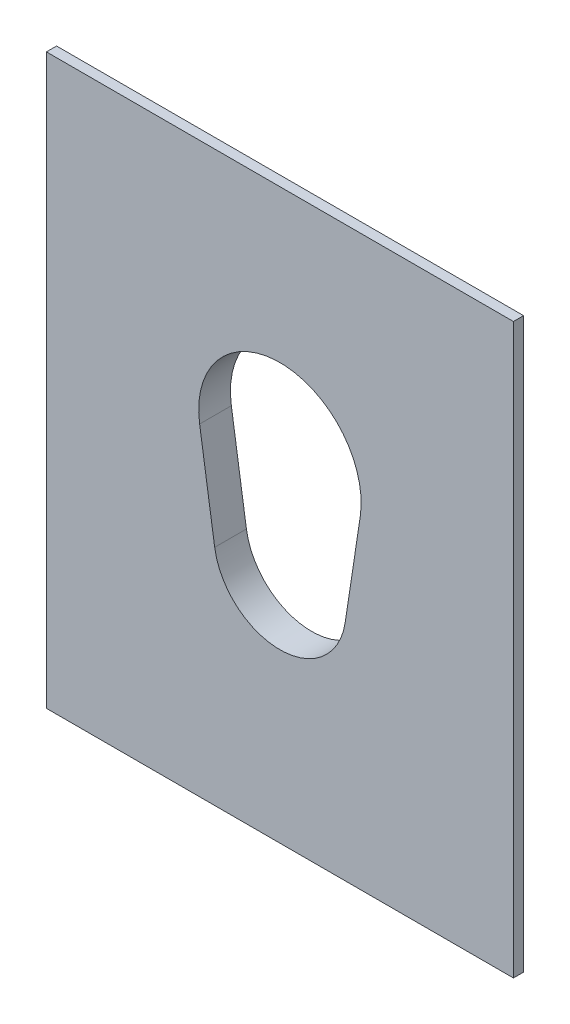
SolidWorks part; units mm, degrees
ref_plane "Front Plane" through (0, 0, 0) normal (0, 0, 1) x (1, 0, 0)
ref_plane "Top Plane" through (0, 0, 0) normal (0, 1, 0) x (1, 0, 0)
ref_plane "Right Plane" through (0, 0, 0) normal (1, 0, 0) x (0, 0, -1)
sketch "Sketch1" plane through (0, 0, 0) normal (0, 0, 1) x (1, 0, 0)
  line L0 (-6.4265, -0.975) -> (-7.9095, 8.8)
  line L1 (6.4265, -0.975) -> (7.9095, 8.8)
  line L4 (0, 10) -> (0, 0) construction
  line L5 (-13, 23) -> (13, 23)
  line L6 (-13, 23) -> (-13, -13)
  line L7 (-13, -13) -> (13, -13)
  line L8 (13, 23) -> (13, -13)
  arc A0 (-6.4265, -0.975) -> (6.4265, -0.975) centre (0, 0) ccw
  arc A1 (-7.9095, 8.8) -> (7.9095, 8.8) centre (0, 10) cw
  point P11 (0, 5)
  point P12 (0, -13)
  point P13 (-13, 5)
  point P14 (0, 18)
  point P15 (-8, 10)
  dimension "D1" = 6.5
  dimension "D2" = 8
  dimension "D3" = 10
  dimension "D4" = 5
  dimension "D5" = 5
extrude "Boss-Extrude1" add sketch "Sketch1" along normal mid plane 3.125
sketch "Sketch2" plane through (0, 0, 1.5625) normal (0, 0, -1) x (-1, 0, 0)
  line L4 (13, -13) -> (13, 23)
  line L5 (-13, -13) -> (13, -13)
  line L6 (-13, 23) -> (-13, -13)
  line L7 (13, 23) -> (-13, 23)
  line L8 (13, -13) -> (13, 23)
  line L9 (-13, -13) -> (13, -13)
  line L10 (-13, 23) -> (-13, -13)
  line L11 (13, 23) -> (-13, 23)
  line L16 (23, -23) -> (23, 33)
  line L17 (-23, -23) -> (23, -23)
  line L18 (-23, 33) -> (-23, -23)
  line L19 (23, 33) -> (-23, 33)
  line L20 (23, -23) -> (23, 33)
  line L21 (-23, -23) -> (23, -23)
  line L22 (-23, 33) -> (-23, -23)
  line L23 (23, 33) -> (-23, 33)
  dimension "D1" = 0
  dimension "D2" = 10
extrude "Boss-Extrude2" add sketch "Sketch2" along normal blind 1
